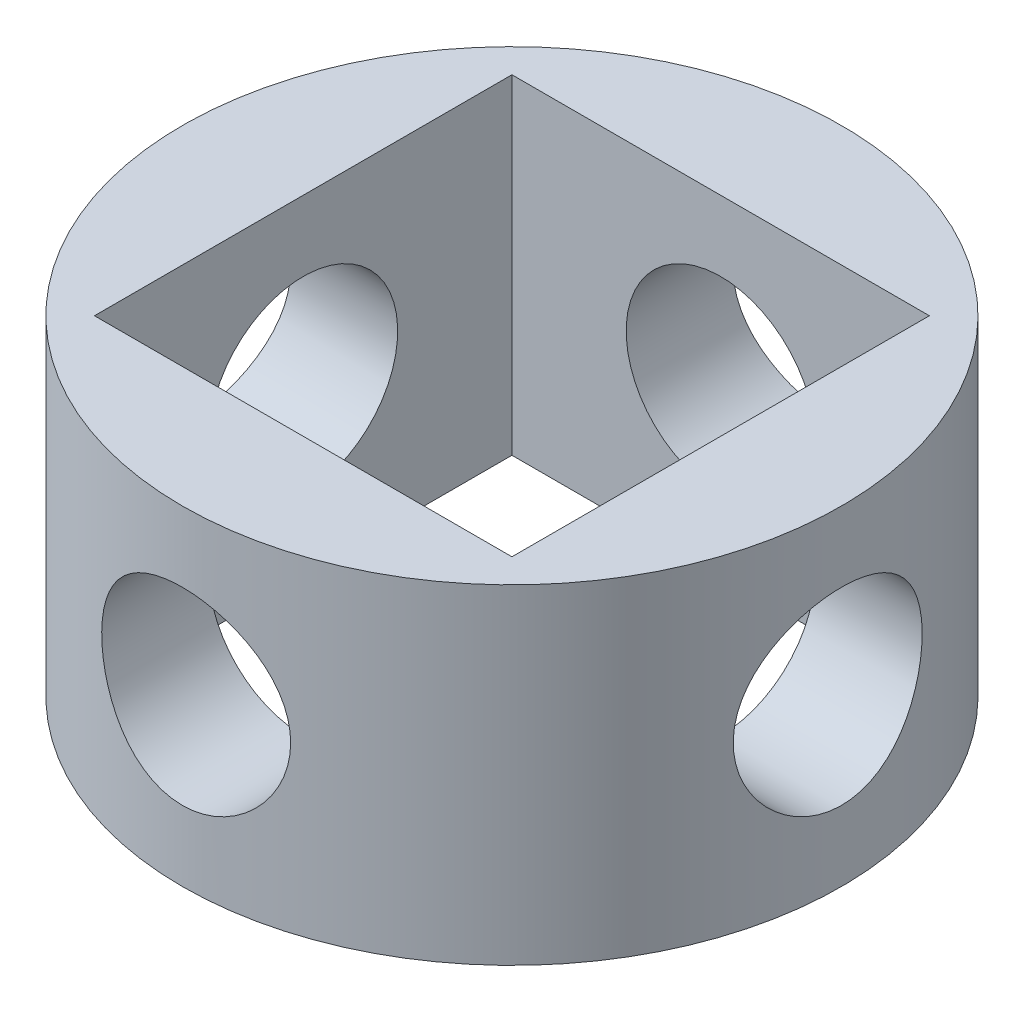
SolidWorks part; units mm, degrees
ref_plane "Front" through (0, 0, 0) normal (0, 0, 1) x (1, 0, 0)
ref_plane "Top" through (0, 0, 0) normal (0, 1, 0) x (1, 0, 0)
ref_plane "Right" through (0, 0, 0) normal (1, 0, 0) x (0, 0, -1)
sketch "Sketch1" plane through (0, 0, 0) normal (0, 1, 0) x (1, 0, 0)
  line L5 (150, -150) -> (-150, 150) construction
  line L6 (150, 150) -> (-150, -150) construction
  circle A0 centre (0, 0) radius 150
  point P0 (0, 0)
  dimension "D1" = 300
  dimension "D2" = 300
extrude "Boss-Extrude1" add sketch "Sketch1" along normal blind 150
sketch "Sketch2" plane through (0, 150, 0) normal (0, 1, 0) x (1, 0, 0)
  line L1 (-95, 95) -> (95, 95)
  line L2 (-95, 95) -> (-95, -95)
  line L3 (-95, -95) -> (95, -95)
  line L4 (95, 95) -> (95, -95)
  line L5 (-95, 95) -> (95, -95) construction
  line L6 (-95, -95) -> (95, 95) construction
  point P0 (0, 0)
  dimension "D1" = 190
  dimension "D2" = 190
extrude "Cut-Extrude1" cut sketch "Sketch2" against normal blind 150 contours L2 L1 L4 L3
sketch "Sketch3" plane through (0, 0, 0) normal (0, 0, 1) x (1, 0, 0)
  circle A0 centre (0, 75) radius 43
  dimension "D1" = 86
extrude "Cut-Extrude2" cut sketch "Sketch3" against normal through all both and the other way through all contours A0
sketch "Sketch4" plane through (0, 0, 0) normal (1, 0, 0) x (0, 0, -1)
  circle A0 centre (0, 75) radius 43
  dimension "D1" = 86
extrude "Cut-Extrude3" cut sketch "Sketch4" against normal through all both and the other way through all contours A0
equation "\"`30\"=10"
